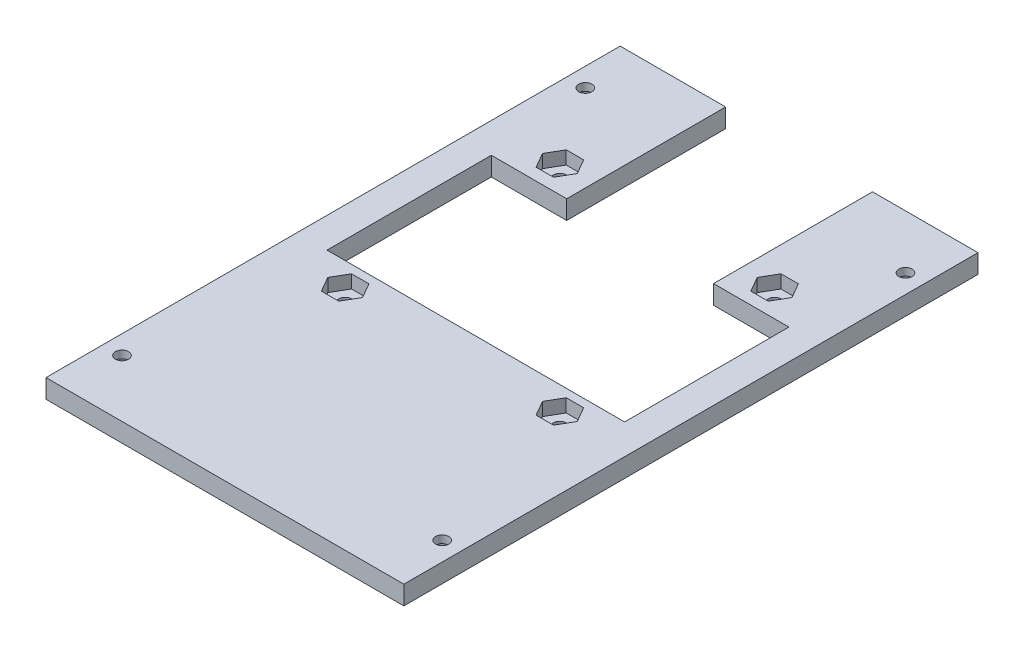
SolidWorks part; units mm, degrees
ref_plane "Front Plane" through (0, 0, 0) normal (0, 0, 1) x (1, 0, 0)
ref_plane "Top Plane" through (0, 0, 0) normal (0, 1, 0) x (1, 0, 0)
ref_plane "Right Plane" through (0, 0, 0) normal (1, 0, 0) x (0, 0, -1)
sketch "Sketch1" plane through (0, 0, 0) normal (0, 1, 0) x (1, 0, 0)
  line L1 (-47.5, 76.21) -> (47.5, 76.21)
  line L2 (-47.5, 76.21) -> (-47.5, -76.21)
  line L3 (-47.5, -76.21) -> (47.5, -76.21)
  line L4 (47.5, 76.21) -> (47.5, -76.21)
  line L5 (0, -76.21) -> (0, 76.21) construction
  line L6 (-47.5, 0) -> (47.5, 0) construction
  point P96 (0, 0)
  dimension "D1" = 152.42
  dimension "D2" = 95
extrude "Boss-Extrude1" add sketch "Sketch1" along normal blind 5
sketch "Sketch2" plane through (0, 0, 0) normal (0, -1, 0) x (1, 0, 0)
  line L0 (42.5, -61.96) -> (42.5, 61.04) construction
  line L1 (42.5, 61.04) -> (-42.5, 61.04) construction
  line L2 (-42.5, 61.04) -> (-42.5, -61.96) construction
  line L3 (-42.5, -61.96) -> (42.5, -61.96) construction
  line L4 (-47.5, 76.21) -> (47.5, 76.21) construction
  line L5 (-47.5, -76.21) -> (-47.5, 76.21) construction
  circle A0 centre (42.5, -61.96) radius 1.75
  circle A1 centre (-42.5, -61.96) radius 1.75
  circle A2 centre (-42.5, 61.04) radius 1.75
  circle A3 centre (42.5, 61.04) radius 1.75
  dimension "D1" = 85
  dimension "D2" = 123
  dimension "D3" = 15.17
  dimension "D4" = 5
  dimension "D5" = 3.5
  dimension "D6" = 3.5
  dimension "D7" = 3.5
  dimension "D8" = 3.5
extrude "Cut-Extrude1" cut sketch "Sketch2" against normal blind 10
sketch "Sketch3" plane through (0, 0, 0) normal (0, -1, 0) x (1, 0, 0)
  line L0 (0, -76.21) -> (0, -39.5869) construction
  line L1 (47.5, -76.21) -> (-47.5, -76.21) construction
  line L2 (47.5, 0) -> (19.7599, 0) construction
  line L3 (47.5, 76.21) -> (47.5, -76.21) construction
  circle A0 centre (42.5, -61.96) radius 3.5
  circle A1 centre (42.5, 61.04) radius 3.5
  circle A2 centre (-42.5, 61.04) radius 3.5
  circle A3 centre (-42.5, -61.96) radius 3.5
  dimension "D1" = 7
  dimension "D2" = 7
  dimension "D3" = 7
  dimension "D4" = 7
extrude "Cut-Extrude2" cut sketch "Sketch3" against normal blind 3
sketch "Sketch4" plane through (0, 0, 0) normal (0, -1, 0) x (1, 0, 0)
  line L1 (28.5, -41.21) -> (-28.5, -41.21) construction
  line L2 (28.5, -41.21) -> (28.5, 15.79) construction
  line L3 (28.5, 15.79) -> (-28.5, 15.79) construction
  line L4 (-28.5, -41.21) -> (-28.5, 15.79) construction
  line L5 (0, 15.79) -> (0, -41.21) construction
  line L6 (28.5, -12.71) -> (-28.5, -12.71) construction
  line L9 (47.5, -76.21) -> (-47.5, -76.21) construction
  line L12 (-47.5, -76.21) -> (-47.5, 76.21) construction
  circle A0 centre (28.5, -41.21) radius 1.75
  circle A1 centre (28.5, 15.79) radius 1.75
  circle A2 centre (-28.5, 15.79) radius 1.75
  circle A3 centre (-28.5, -41.21) radius 1.75
  point P4 (0, 0)
  dimension "D3" = 3.5
  dimension "D4" = 3.5
  dimension "D5" = 3.5
  dimension "D6" = 3.5
  dimension "D1" = 57
  dimension "D2" = 57
  dimension "D7" = 35
  dimension "D8" = 19
sketch "Sketch5" plane through (0, 0, 0) normal (0, -1, 0) x (1, 0, 0)
  line L0 (47.5, 76.21) -> (47.5, -76.21) construction
  line L5 (39.5, -34.01) -> (19.5, -34.01)
  line L7 (39.5, -34.01) -> (39.5, 9.61)
  line L19 (39.5, 9.61) -> (-39.5, 9.61)
  line L20 (-39.5, -34.01) -> (-39.5, 9.61)
  line L29 (0, 9.61) -> (0, -34.01) construction
  line L34 (39.5, -12.2) -> (-39.5, -12.2) construction
  line L35 (47.5, -76.21) -> (-47.5, -76.21) construction
  line L36 (19.5, -76.21) -> (-19.5, -76.21)
  line L37 (19.5, -76.21) -> (19.5, -34.01)
  line L39 (-19.5, -76.21) -> (-19.5, -34.01)
  line L40 (0, -55.11) -> (0, -76.21) construction
  line L41 (19.5, -55.11) -> (-19.5, -55.11) construction
  line L42 (-47.5, -76.21) -> (-47.5, 76.21) construction
  line L48 (-47.5, 76.21) -> (47.5, 76.21) construction
  line L56 (-19.5, -34.01) -> (-39.5, -34.01)
  circle A2 centre (28.5, -41.21) radius 1.75 construction
  circle A3 centre (-28.5, -41.21) radius 1.75 construction
  point P18 (0, 0)
  point P19 (0, 0)
  point P22 (0, 76.21)
  point P261 (0, -55.11)
  point P439 (0, -12.2)
  dimension "D1" = 9
  dimension "D2" = 9
  dimension "D3" = 8
  dimension "D4" = 8
  dimension "D5" = 66.6
  dimension "D12" = 42.2
extrude "Cut-Extrude3" cut sketch "Sketch5" against normal blind 10
extrude "Cut-Extrude4" cut sketch "Sketch4" against normal blind 10
sketch "Sketch6" plane through (0, 5, 0) normal (0, 1, 0) x (1, 0, 0)
  line L1 (-26.1906, 45.21) -> (-30.8094, 45.21)
  line L2 (-30.8094, 45.21) -> (-33.1188, 41.21)
  line L3 (-33.1188, 41.21) -> (-30.8094, 37.21)
  line L4 (-30.8094, 37.21) -> (-26.1906, 37.21)
  line L5 (-26.1906, 37.21) -> (-23.8812, 41.21)
  line L6 (-23.8812, 41.21) -> (-26.1906, 45.21)
  line L7 (30.8094, 45.21) -> (26.1906, 45.21)
  line L8 (26.1906, 45.21) -> (23.8812, 41.21)
  line L9 (23.8812, 41.21) -> (26.1906, 37.21)
  line L10 (26.1906, 37.21) -> (30.8094, 37.21)
  line L11 (30.8094, 37.21) -> (33.1188, 41.21)
  line L12 (33.1188, 41.21) -> (30.8094, 45.21)
  line L13 (30.8094, -11.79) -> (26.1906, -11.79)
  line L14 (26.1906, -11.79) -> (23.8812, -15.79)
  line L15 (23.8812, -15.79) -> (26.1906, -19.79)
  line L16 (26.1906, -19.79) -> (30.8094, -19.79)
  line L17 (30.8094, -19.79) -> (33.1188, -15.79)
  line L18 (33.1188, -15.79) -> (30.8094, -11.79)
  line L19 (-26.1906, -19.79) -> (-23.8812, -15.79)
  line L20 (-23.8812, -15.79) -> (-26.1906, -11.79)
  line L21 (-26.1906, -11.79) -> (-30.8094, -11.79)
  line L22 (-30.8094, -11.79) -> (-33.1188, -15.79)
  line L23 (-33.1188, -15.79) -> (-30.8094, -19.79)
  line L24 (-30.8094, -19.79) -> (-26.1906, -19.79)
  circle A0 centre (-28.5, 41.21) radius 4 construction
  circle A1 centre (28.5, 41.21) radius 4 construction
  circle A2 centre (28.5, -15.79) radius 4 construction
  circle A3 centre (-28.5, -15.79) radius 4 construction
  dimension "D1" = 8
  dimension "D2" = 8
  dimension "D3" = 8
  dimension "D4" = 8
extrude "Cut-Extrude5" cut sketch "Sketch6" against normal blind 3.5
